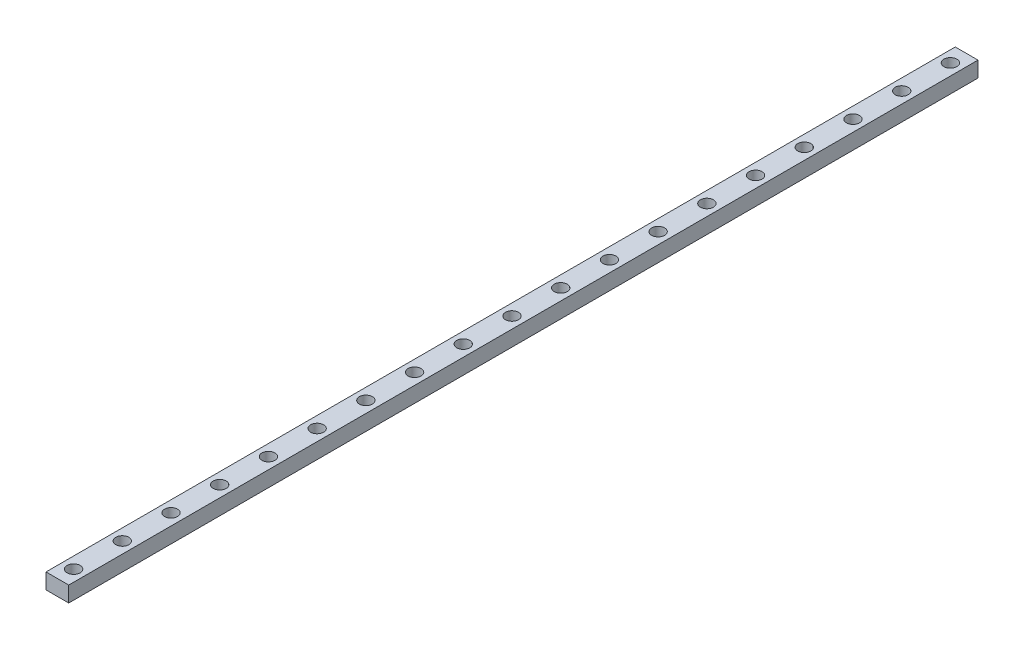
SolidWorks part; units mm, degrees
ref_plane "前视基准面" through (0, 0, 0) normal (0, 0, 1) x (1, 0, 0)
ref_plane "上视基准面" through (0, 0, 0) normal (0, 1, 0) x (1, 0, 0)
ref_plane "右视基准面" through (0, 0, 0) normal (1, 0, 0) x (0, 0, -1)
sketch "草图1" plane through (0, 0, 0) normal (0, 0, 1) x (1, 0, 0)
  line L1 (-3.5, 2.4) -> (3.5, 2.4)
  line L2 (-3.5, 2.4) -> (-3.5, -2.4)
  line L3 (-3.5, -2.4) -> (3.5, -2.4)
  line L4 (3.5, 2.4) -> (3.5, -2.4)
  line L5 (-3.5, 2.4) -> (3.5, -2.4) construction
  line L6 (-3.5, -2.4) -> (3.5, 2.4) construction
  point P0 (0, 0)
  dimension "D1" = 4.8
  dimension "D2" = 7
extrude "凸台-拉伸1" add sketch "草图1" along normal blind 280
sketch "草图2" plane through (0, 2.4, 0) normal (0, 1, 0) x (1, 0, 0)
  line L0 (3.5, 0) -> (-3.5, 0) construction
  circle A0 centre (0, -5) radius 2
  dimension "D2" = 4
  dimension "D1" = 5
extrude "切除-拉伸1" cut sketch "草图2" against normal blind 3
sketch "草图3" plane through (0, -0.6, 0) normal (0, 1, 0) x (1, 0, 0)
  circle A0 centre (0, -5) radius 1
  dimension "D1" = 2
extrude "切除-拉伸2" cut sketch "草图3" against normal blind 3
pattern_linear "阵列(线性)1" count 19 spacing 15 along (0, 0, 1) of "切除-拉伸2"
pattern_linear "阵列(线性)2" count 19 spacing 15 along (0, 0, 1) of "切除-拉伸1"
